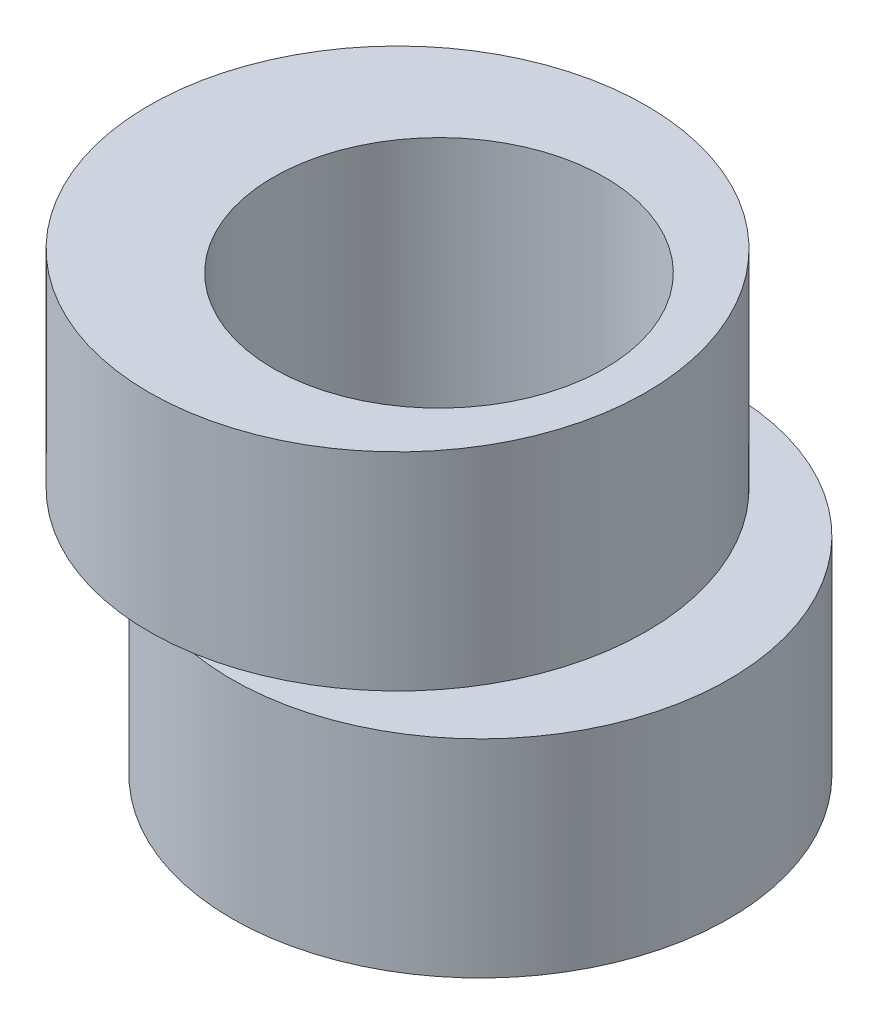
SolidWorks part; units mm, degrees
ref_plane "Front Plane" through (0, 0, 0) normal (0, 0, 1) x (1, 0, 0)
ref_plane "Top Plane" through (0, 0, 0) normal (0, 1, 0) x (1, 0, 0)
ref_plane "Right Plane" through (0, 0, 0) normal (1, 0, 0) x (0, 0, -1)
sketch "Sketch1" plane through (0, 0, 0) normal (0, 1, 0) x (1, 0, 0)
  line L0 (0, 0) -> (-9287.0331, 0) construction
  line L1 (0, 0) -> (0, -9287.0331) construction
  circle A0 centre (0, 0) radius 4
  circle A1 centre (1, 0) radius 6
  dimension "D1" = 8
  dimension "D2" = 1
  dimension "D3" = 12
extrude "Boss-Extrude1" add sketch "Sketch1" along normal blind 5
sketch "Sketch2" plane through (0, 5, 0) normal (0, 1, 0) x (1, 0, 0)
  line L0 (0, 0) -> (-50000, 0) construction
  line L1 (0, 0) -> (0, -50000) construction
  circle A0 centre (0, 0) radius 4
  circle A2 centre (-1, 0) radius 6
  dimension "D1" = 8
  dimension "D2" = 12
  dimension "D3" = 1
extrude "Boss-Extrude2" add sketch "Sketch2" along normal blind 5
